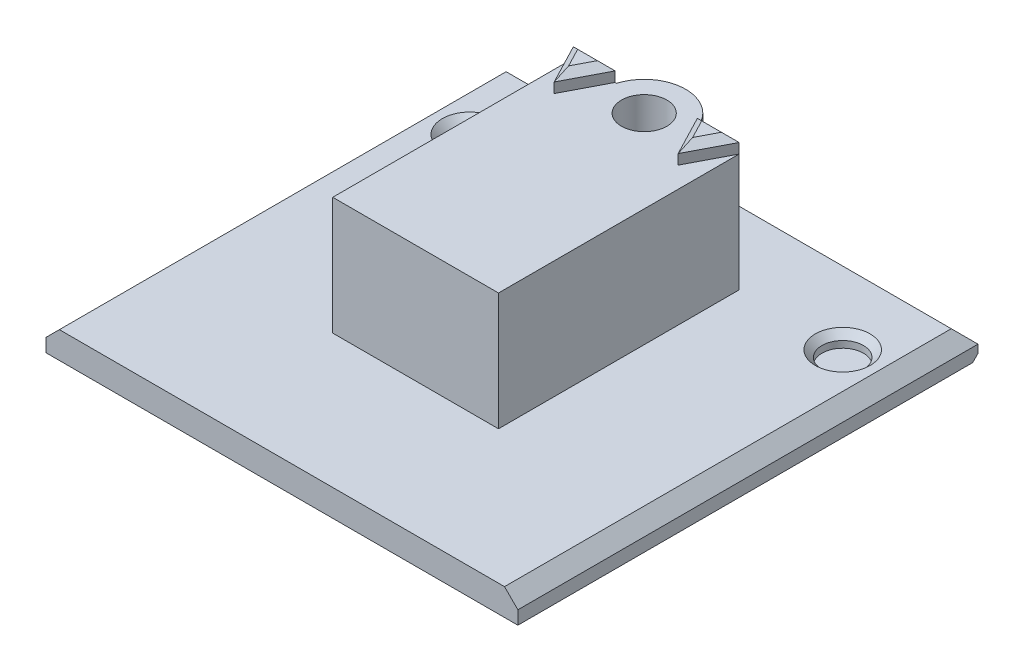
SolidWorks part; units mm, degrees
ref_plane "Front Plane" through (0, 0, 0) normal (0, 0, 1) x (1, 0, 0)
ref_plane "Top Plane" through (0, 0, 0) normal (0, 1, 0) x (1, 0, 0)
ref_plane "Right Plane" through (0, 0, 0) normal (1, 0, 0) x (0, 0, -1)
sketch "Sketch1" plane through (0, 0, 0) normal (0, 1, 0) x (1, 0, 0)
  line L5 (0, 0) -> (35.3, 0)
  line L6 (0, 0) -> (0, 34.42)
  line L7 (0, 34.42) -> (35.3, 34.42)
  line L8 (35.3, 0) -> (35.3, 34.42)
  dimension "D1" = 35.3
  dimension "D2" = 34.42
extrude "Boss-Extrude1" add sketch "Sketch1" along normal blind 2
sketch "Sketch2" plane through (0, 2, 0) normal (0, 1, 0) x (1, 0, 0)
  line L0 (17.65, 34.42) -> (17.65, 0) construction
  line L1 (35.3, 34.42) -> (0, 34.42) construction
  line L2 (0, 0) -> (35.3, 0) construction
  line L3 (14.6835, 28) -> (17.65, 28) construction
  line L4 (11.45, 28) -> (14.6835, 28)
  line L5 (11.45, 28) -> (11.45, 10)
  line L6 (11.45, 10) -> (23.85, 10)
  line L7 (23.85, 28) -> (23.85, 10)
  line L8 (11.45, 28) -> (23.85, 10) construction
  line L9 (11.45, 10) -> (23.85, 28) construction
  line L10 (20.6165, 28) -> (23.85, 28)
  line L11 (17.65, 28) -> (20.6165, 28) construction
  arc A0 (20.6165, 28) -> (14.6835, 28) centre (17.65, 27.1) ccw
  circle A1 centre (17.65, 27.1) radius 1.6719 construction
  point P6 (17.65, 19)
  dimension "D4" = 6.2
  dimension "D1" = 10
  dimension "D2" = 18
  dimension "D3" = 12.4
  dimension "D5" = 0.9
extrude "Boss-Extrude2" add sketch "Sketch2" along normal blind 8.8
sketch "Sketch3" plane through (0, 10.8, 0) normal (0, 1, 0) x (1, 0, 0)
  line L0 (17.65, 10) -> (17.65, 30.2) construction
  line L1 (22.2883, 25) -> (17.65, 25) construction
  line L2 (14.5734, 28) -> (13.0117, 25)
  line L3 (11.45, 10) -> (23.85, 10) construction
  line L4 (11.45, 28) -> (13.0117, 25)
  line L5 (14.5734, 28) -> (11.45, 28)
  line L10 (23.85, 28) -> (22.2883, 25)
  line L11 (22.2883, 25) -> (22.2883, 28) construction
  line L12 (23.85, 28) -> (20.6165, 28) construction
  line L13 (20.7266, 28) -> (23.85, 28)
  line L14 (22.2883, 25) -> (23.85, 25) construction
  line L15 (23.85, 10) -> (23.85, 28) construction
  line L16 (23.85, 25) -> (23.85, 28) construction
  line L17 (20.7266, 28) -> (22.2883, 25)
  arc A0 (20.6165, 28) -> (14.6835, 28) centre (17.65, 27.1) ccw construction
  circle A1 centre (17.65, 27.1) radius 2.1 construction
  dimension "D2" = 4.2
  dimension "D1" = 62.5
sketch "Sketch4" plane through (0, 2, 0) normal (0, 1, 0) x (1, 0, 0)
  line L0 (35.3, 34.42) -> (0, 34.42) construction
  line L1 (0, 0) -> (35.3, 0) construction
  line L2 (17.65, 0) -> (17.65, 34.42) construction
  circle A0 centre (3.7, 28) radius 1.55
  circle A1 centre (31.6, 28) radius 1.55
  dimension "D3" = 3.1
  dimension "D1" = 6.42
  dimension "D2" = 13.95
extrude "Cut-Extrude2" cut sketch "Sketch4" against normal blind 1
chamfer "Chamfer4" distance 0.5 angle 45 2 edges at (31.6, 2, -29.55) (3.7, 2, -26.45)
extrude "Boss-Extrude3" add sketch "Sketch3" along normal blind 1.25
sketch "Sketch7" plane through (0, 10.8, 0) normal (0, 1, 0) x (1, 0, 0)
  circle A0 centre (17.65, 27.1) radius 1.7
  dimension "D1" = 3.4
extrude "Cut-Extrude6" cut sketch "Sketch7" against normal through all
sketch "Sketch6" plane through (0, 0, 0) normal (0, -1, 0) x (1, 0, 0)
  circle A0 centre (17.65, -27.1) radius 2.85
  dimension "D1" = 5.7
extrude "Cut-Extrude5" cut sketch "Sketch6" against normal blind 3
chamfer "Chamfer5" distance 0.5 angle 45 6 edges at (12.2309, 12.05, -26.5) (13.0117, 12.05, -28) (13.7926, 12.05, -26.5) (21.5074, 12.05, -26.5) (22.2883, 12.05, -28) (23.0691, 12.05, -26.5)
chamfer "Chamfer3" distance 1 angle 45 3 edges at (35.3, 2, -17.21) (0, 2, -17.21) (17.65, 2, -34.42)
chamfer "Chamfer6" distance 0.4 angle 45 1 edges at (17.65, 0, -34.42)
